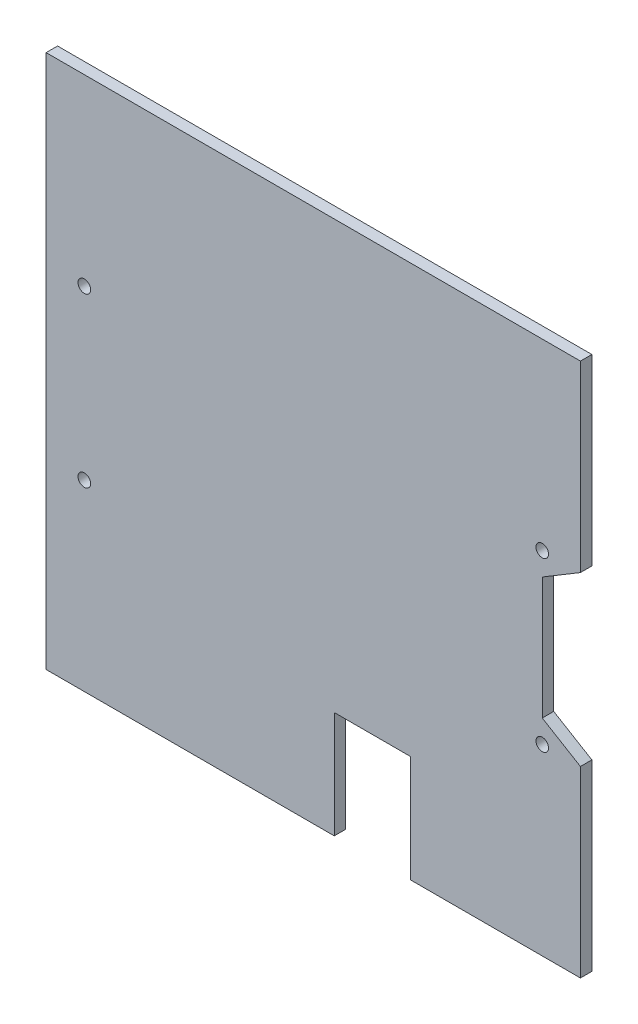
SolidWorks part; units mm, degrees
ref_plane "Front Plane" through (0, 0, 0) normal (0, 0, 1) x (1, 0, 0)
ref_plane "Top Plane" through (0, 0, 0) normal (0, 1, 0) x (1, 0, 0)
ref_plane "Right Plane" through (0, 0, 0) normal (1, 0, 0) x (0, 0, -1)
sketch "Sketch1" plane through (0, 0, 0) normal (0, 0, 1) x (1, 0, 0)
  line L0 (0, -26) -> (75.5, -26)
  line L1 (140, 114) -> (140, 66)
  line L2 (0, 114) -> (0, -26)
  line L3 (130, 60) -> (140, 66)
  line L4 (0, 114) -> (140, 114)
  line L5 (130, 60) -> (130, 28)
  line L6 (130, 28) -> (140, 22)
  line L7 (140, -26) -> (140, 22)
  line L8 (10, 22) -> (130, 22) construction
  line L9 (130, 44) -> (0, 44) construction
  line L10 (95.5, -26) -> (140, -26)
  line L11 (85.5, 2) -> (85.5, 95.2594) construction
  line L12 (75.5, -26) -> (75.5, 2)
  line L13 (75.5, 2) -> (95.5, 2)
  line L14 (95.5, -26) -> (95.5, 2)
  circle A0 centre (10, 22) radius 1.65
  circle A1 centre (130, 66) radius 1.65
  circle A2 centre (130, 22) radius 1.65
  circle A3 centre (10, 66) radius 1.65
  dimension "D4" = 10
  dimension "D9" = 3.3
  dimension "D1" = 140
  dimension "D2" = 140
  dimension "D3" = 22
  dimension "D5" = 120
  dimension "D6" = 44
  dimension "D7" = 130
  dimension "D8" = 32
  dimension "D10" = 20
  dimension "D11" = 44.5
  dimension "D12" = 28
extrude "Boss-Extrude1" add sketch "Sketch1" along normal blind 3
